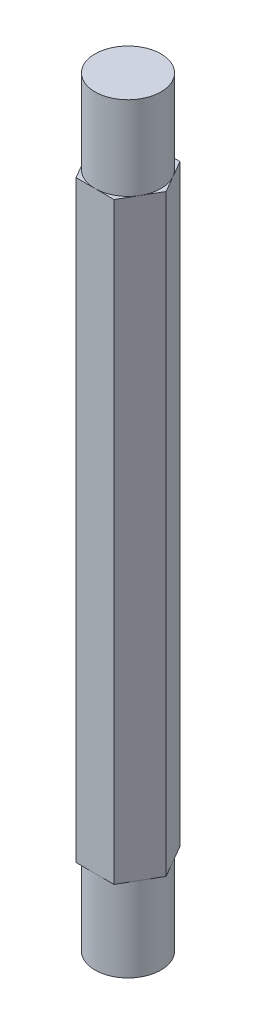
SolidWorks part; units mm, degrees
material "Plain Carbon Steel"
ref_plane "Front Plane" through (0, 0, 0) normal (0, 0, 1) x (1, 0, 0)
ref_plane "Top Plane" through (0, 0, 0) normal (0, 1, 0) x (1, 0, 0)
ref_plane "Right Plane" through (0, 0, 0) normal (1, 0, 0) x (0, 0, -1)
sketch "Sketch1" plane through (0, 0, 0) normal (0, 1, 0) x (1, 0, 0)
  line L1 (2.8868, 0) -> (1.4434, 2.5)
  line L2 (1.4434, 2.5) -> (-1.4434, 2.5)
  line L3 (-1.4434, 2.5) -> (-2.8868, 0)
  line L4 (-2.8868, 0) -> (-1.4434, -2.5)
  line L5 (-1.4434, -2.5) -> (1.4434, -2.5)
  line L6 (1.4434, -2.5) -> (2.8868, 0)
  circle A0 centre (0, 0) radius 2.5 construction
extrude "Boss-Extrude1" add sketch "Sketch1" along normal blind 57.7
sketch "Sketch2" plane through (0, 0, 0) normal (0, -1, 0) x (-1, 0, 0)
  circle A1 centre (0, 0) radius 2.8868
  circle A2 centre (0, 0) radius 2.5
  line M3 (-2.8868, 0) -> (-1.4434, -2.5)
  line M4 (-1.4434, -2.5) -> (1.4434, -2.5)
  line M5 (1.4434, -2.5) -> (2.8868, 0)
  line M6 (2.8868, 0) -> (1.4434, 2.5)
  line M7 (1.4434, 2.5) -> (-1.4434, 2.5)
  line M8 (-1.4434, 2.5) -> (-2.8868, 0)
extrude "Cut-Extrude1" cut sketch "Sketch2" against normal blind 6.35 contours A2 M3 M4 | A2 M4 M5 | A2 M5 M6 | A2 M6 M7 | A2 M8 M3 | A2 M7 M8
ref_plane "Symmetry" through (0, 28.85, 0) normal (0, -1, 0) x (-1, 0, 0)
mirror "Mirror1" about plane through (0, 28.85, 0) normal (0, -1, 0) of "Cut-Extrude1"
